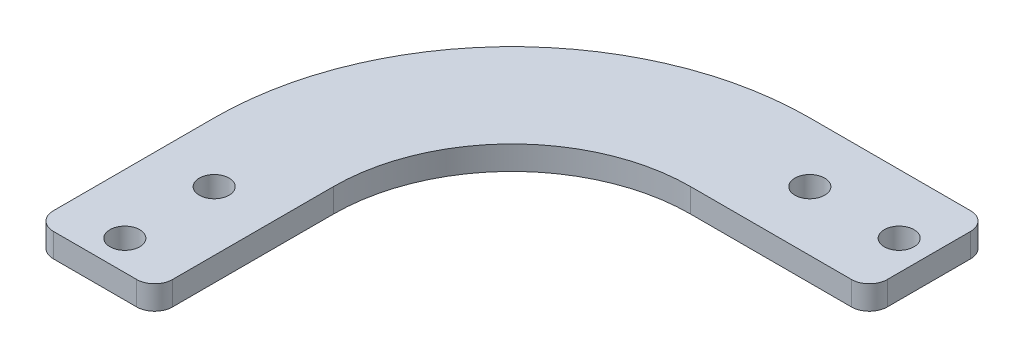
SolidWorks part; units mm, degrees
material "Thornel Mat VMA"
ref_plane "Front Plane" through (0, 0, 0) normal (0, 0, 1) x (1, 0, 0)
ref_plane "Top Plane" through (0, 0, 0) normal (0, 1, 0) x (1, 0, 0)
ref_plane "Right Plane" through (0, 0, 0) normal (1, 0, 0) x (0, 0, -1)
sketch "Sketch1" plane through (0, 0, 0) normal (0, 1, 0) x (1, 0, 0)
  line L2 (0, 30.7616) -> (0, -31.9345) construction
  line L3 (-37.514, 0) -> (35.3317, 0) construction
  line L4 (-50, 0) -> (-50, -27)
  line L5 (-47, -30) -> (-33, -30)
  line L6 (-30, -27) -> (-30, -14.1421)
  line L7 (0, 50) -> (27, 50)
  line L8 (30, 47) -> (30, 33)
  line L9 (27, 30) -> (14.1421, 30)
  line L11 (-40, -30) -> (-40, 24.2665) construction
  line L12 (30, 40) -> (-23.5548, 40) construction
  line L13 (-30, -14.1421) -> (-30, 0)
  line L14 (0, 30) -> (14.1421, 30)
  arc A1 (0, 50) -> (-50, 0) centre (0, 0) ccw
  arc A4 (27, 50) -> (30, 47) centre (27, 47) cw
  arc A5 (30, 33) -> (27, 30) centre (27, 33) cw
  arc A6 (-33, -30) -> (-30, -27) centre (-33, -27) ccw
  arc A7 (-50, -27) -> (-47, -30) centre (-47, -27) ccw
  circle A8 centre (-40, -10) radius 2.5
  circle A9 centre (-40, -25) radius 2.5
  circle A10 centre (10, 40) radius 2.5
  circle A11 centre (25, 40) radius 2.5
  arc A12 (0, 30) -> (-30, 0) centre (0, 0) ccw
  point P16 (-30, -10)
  point P19 (10, 30)
  point P22 (30, 50)
  point P25 (30, 30)
  point P28 (-30, -30)
  point P31 (-50, -30)
  dimension "D1" = 100
  dimension "D2" = 20
  dimension "D8" = 20
  dimension "D9" = 3
  dimension "D10" = 5
  dimension "D11" = 5
  dimension "D14" = 5
  dimension "D15" = 5
  dimension "D3" = 30
  dimension "D4" = 20
  dimension "D5" = 30
  dimension "D6" = 20
  dimension "D7" = 20
  dimension "D12" = 10
  dimension "D13" = 25
  dimension "D16" = 10
  dimension "D17" = 25
extrude "Boss-Extrude1" add sketch "Sketch1" along normal blind 4
